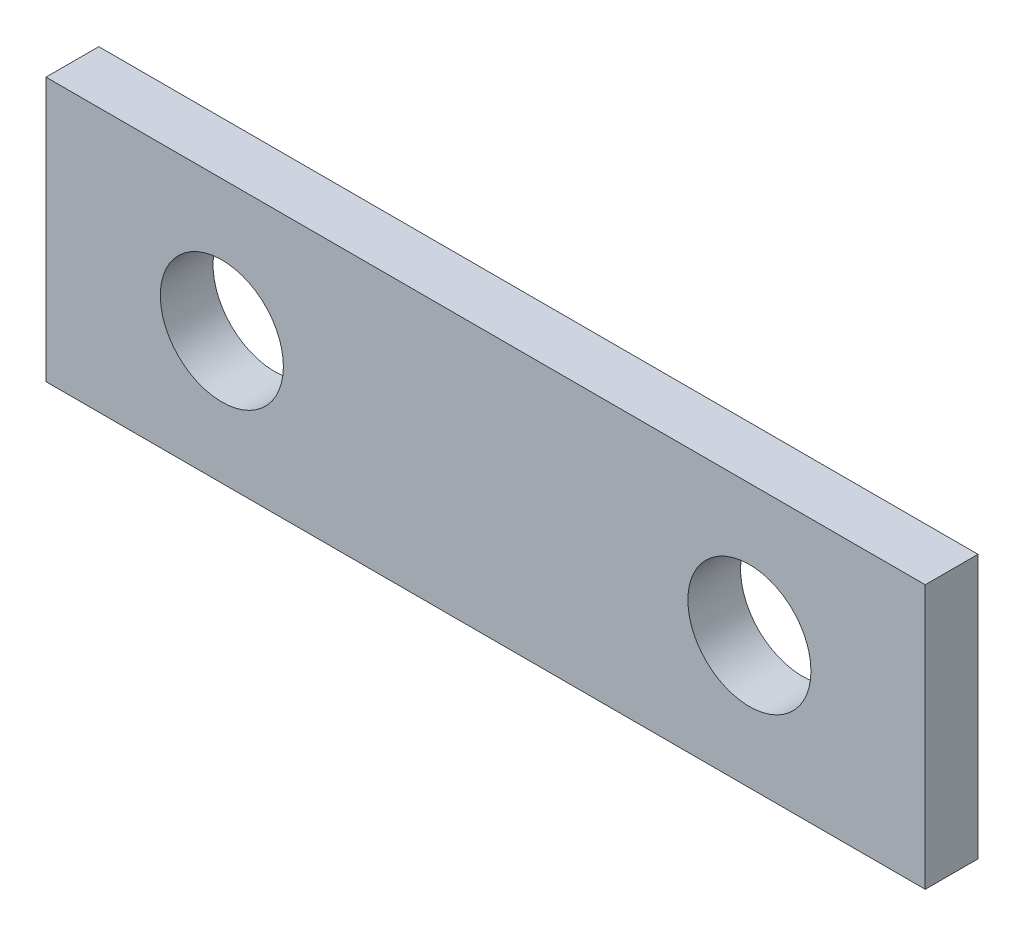
SolidWorks part; units mm, degrees
ref_plane "前视基准面" through (0, 0, 0) normal (0, 0, 1) x (1, 0, 0)
ref_plane "上视基准面" through (0, 0, 0) normal (0, 1, 0) x (1, 0, 0)
ref_plane "右视基准面" through (0, 0, 0) normal (1, 0, 0) x (0, 0, -1)
sketch "草图1" plane through (0, 0, 0) normal (0, 0, 1) x (1, 0, 0)
  line L0 (-1000, 15) -> (49000, 15) construction
  line L1 (0, 0) -> (100, 0)
  line L2 (0, 0) -> (0, 30)
  line L3 (0, 30) -> (100, 30)
  line L4 (100, 0) -> (100, 30)
  line L5 (50, -970) -> (50, 49030) construction
  circle A0 centre (20, 15) radius 7
  circle A1 centre (80, 15) radius 7
  point P8 (0, 15)
  point P15 (50, 30)
  dimension "D4" = 14
  dimension "D1" = 100
  dimension "D2" = 30
  dimension "D3" = 60
extrude "凸台-拉伸1" add sketch "草图1" along normal blind 6
